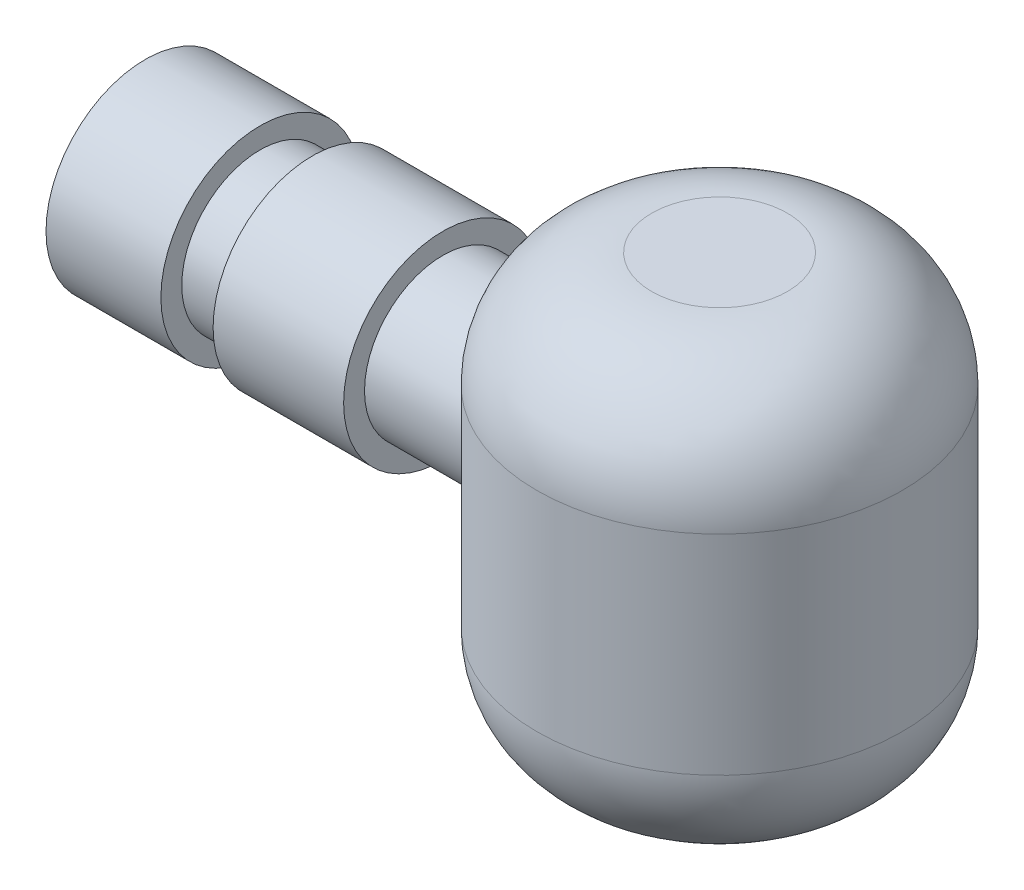
SolidWorks part; units mm, degrees
material "45"
ref_plane "前视基准面" through (0, 0, 0) normal (0, 0, 1) x (1, 0, 0)
ref_plane "上视基准面" through (0, 0, 0) normal (0, 1, 0) x (1, 0, 0)
ref_plane "右视基准面" through (0, 0, 0) normal (1, 0, 0) x (0, 0, -1)
sketch "草图1" plane through (0, 0, 0) normal (0, 0, 1) x (1, 0, 0)
  line L0 (0, 0) -> (153.8206, 0) construction
  line L1 (0, 0) -> (0, 19)
  line L2 (0, 19) -> (22, 19)
  line L3 (22, 19) -> (22, 15)
  line L4 (22, 15) -> (32, 15)
  line L5 (32, 15) -> (32, 19)
  line L6 (32, 19) -> (57, 19)
  line L7 (57, 19) -> (57, 15)
  line L8 (57, 15) -> (112, 15)
  line L9 (112, 15) -> (112, 0)
  line L10 (0, 0) -> (112, 0)
  dimension "D1" = 38
  dimension "D2" = 22
  dimension "D3" = 10
  dimension "D4" = 25
  dimension "D5" = 4
  dimension "D6" = 90
revolve "旋转1" add sketch "草图1" angle 360 about L0
sketch "草图2" plane through (0, 0, 0) normal (0, 1, 0) x (1, 0, 0)
  line L0 (22, -15) -> (22, 15) construction
  line L1 (110, 0) -> (0, 0) construction
  circle A0 centre (110, 0) radius 35
  dimension "D1" = 70
  dimension "D2" = 88
extrude "凸台-拉伸1" add sketch "草图2" along normal mid plane 84
fillet "圆角2" radius 22 2 edges at (110, -42, 35) (110, 42, 35)
sketch "草图3" plane through (0, 0, 0) normal (-1, 0, 0) x (0, 0, 1)
  circle A0 centre (0, 0) radius 16
  dimension "D1" = 32
extrude "切除-拉伸1" cut sketch "草图3" against normal blind 20
